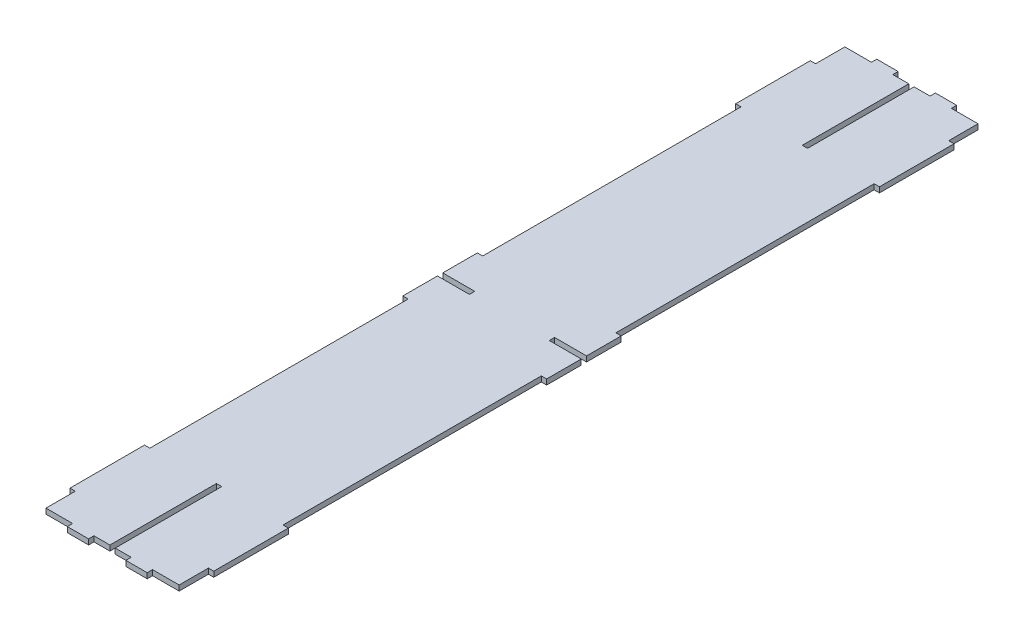
SolidWorks part; units mm, degrees
ref_plane "Front Plane" through (0, 0, 0) normal (0, 0, 1) x (1, 0, 0)
ref_plane "Top Plane" through (0, 0, 0) normal (0, 1, 0) x (1, 0, 0)
ref_plane "Right Plane" through (0, 0, 0) normal (1, 0, 0) x (0, 0, -1)
sketch "Sketch1" plane through (0, 0, 0) normal (0, 1, 0) x (1, 0, 0)
  line L5 (-12.5, 75) -> (-7.5, 75)
  line L6 (-12.5, 75) -> (12.5, 75) construction
  line L21 (-12.5, 75) -> (-12.5, -75) construction
  line L35 (-12.5, -75) -> (12.5, -75) construction
  line L84 (12.5, 75) -> (12.5, -75) construction
  line L85 (-12.5, 75) -> (12.5, -75) construction
  line L86 (-12.5, -75) -> (12.5, 75) construction
  line L87 (-7.5, 75) -> (-7.5, 76)
  line L88 (-7.5, 76) -> (-3.5, 76)
  line L89 (-3.5, 76) -> (-3.5, 75)
  line L91 (3.5, 75) -> (3.5, 76)
  line L92 (3.5, 76) -> (7.5, 76)
  line L93 (7.5, 76) -> (7.5, 75)
  line L94 (7.5, 75) -> (12.5, 75)
  line L95 (-12.5, 75) -> (-13.5, 75) construction
  line L96 (-13.5, 75) -> (-13.5, -75) construction
  line L97 (-13.5, -75) -> (-12.5, -75) construction
  line L98 (-0.5, 75) -> (-0.5, 55)
  line L99 (0, 0) -> (0, 55) construction
  line L100 (-12.5, 75) -> (-12.5, 69.5)
  line L101 (-12.5, 69.5) -> (-13.5, 69.5)
  line L102 (-13.5, 69.5) -> (-13.5, 55.5)
  line L103 (-13.5, 55.5) -> (-12.5, 55.5)
  line L104 (-12.5, 55.5) -> (-12.5, 7)
  line L105 (-12.5, 7) -> (-13.5, 7)
  line L107 (-13.5, -7) -> (-12.5, -7)
  line L108 (-12.5, -7) -> (-12.5, -55.5)
  line L109 (-12.5, -55.5) -> (-13.5, -55.5)
  line L110 (-13.5, -55.5) -> (-13.5, -69.5)
  line L111 (-13.5, -69.5) -> (-12.5, -69.5)
  line L112 (-12.5, -69.5) -> (-12.5, -75)
  line L113 (-13.5, 0) -> (-12.5, 0) construction
  line L114 (12.5, -69.5) -> (12.5, -75)
  line L119 (-0.5, 55) -> (0.5, 55)
  line L120 (0.5, 55) -> (0.5, 75)
  line L125 (-3.5, 75) -> (-0.5, 75)
  line L126 (0.5, 75) -> (3.5, 75)
  line L127 (13.5, -69.5) -> (12.5, -69.5)
  line L128 (13.5, -55.5) -> (13.5, -69.5)
  line L129 (12.5, -55.5) -> (13.5, -55.5)
  line L130 (12.5, -7) -> (12.5, -55.5)
  line L131 (13.5, -7) -> (12.5, -7)
  line L133 (12.5, 7) -> (13.5, 7)
  line L134 (12.5, 55.5) -> (12.5, 7)
  line L135 (13.5, 55.5) -> (12.5, 55.5)
  line L136 (13.5, 69.5) -> (13.5, 55.5)
  line L137 (12.5, 69.5) -> (13.5, 69.5)
  line L138 (12.5, 75) -> (12.5, 69.5)
  line L139 (7.5, -75) -> (12.5, -75)
  line L140 (7.5, -76) -> (7.5, -75)
  line L141 (3.5, -76) -> (7.5, -76)
  line L142 (3.5, -75) -> (3.5, -76)
  line L144 (-3.5, -76) -> (-3.5, -75)
  line L145 (-7.5, -76) -> (-3.5, -76)
  line L146 (-7.5, -75) -> (-7.5, -76)
  line L147 (-12.5, -75) -> (-7.5, -75)
  line L148 (0, 75) -> (0, 55) construction
  line L149 (-3.5, -75) -> (-0.5, -75)
  line L150 (-0.5, -75) -> (-0.5, -55)
  line L151 (-0.5, -55) -> (0.5, -55)
  line L152 (0.5, -55) -> (0.5, -75)
  line L153 (0.5, -75) -> (3.5, -75)
  line L154 (0, -75) -> (0, -55) construction
  line L155 (0, -55) -> (0, 0) construction
  line L156 (-13.5, 0.5) -> (-7.5, 0.5)
  line L157 (-7.5, 0.5) -> (-7.5, -0.5)
  line L158 (-7.5, -0.5) -> (-13.5, -0.5)
  line L159 (-13.5, 7) -> (-13.5, 0.5)
  line L160 (-13.5, -0.5) -> (-13.5, -7)
  line L161 (-12.5, 0) -> (-7.5, 0) construction
  line L162 (-7.5, 0) -> (0, 0) construction
  line L163 (13.5, 7) -> (13.5, 0.5)
  line L164 (13.5, 0.5) -> (7.5, 0.5)
  line L165 (7.5, 0.5) -> (7.5, -0.5)
  line L166 (7.5, -0.5) -> (13.5, -0.5)
  line L167 (13.5, -0.5) -> (13.5, -7)
  line L168 (7.5, 0) -> (0, 0) construction
  line L169 (13.5, 0.5) -> (13.5, -0.5) construction
  line L170 (7.5, 0) -> (12.5, 0) construction
  line L171 (12.5, 0) -> (13.5, 0) construction
  line L172 (-3.5, -76) -> (3.5, -76) construction
  line L173 (0, -75) -> (0, -76) construction
  line L174 (-7.5, -75) -> (-7.5, 75) construction
  point P0 (0, 0)
  point P75 (0, 0)
  point P77 (-7.5, -75.3649)
  point P78 (2.2964, -75)
  dimension "D1" = 25
  dimension "D2" = 150
  dimension "D8" = 5.5
  dimension "D13" = 20
  dimension "D3" = 5
  dimension "D4" = 5
  dimension "D5" = 4
  dimension "D6" = 4
  dimension "D7" = 1
  dimension "D9" = 14
  dimension "D10" = 5.5
  dimension "D11" = 1
  dimension "D12" = 1
  dimension "D14" = 1
  dimension "D15" = 20
  dimension "D16" = 5
  dimension "D17" = 1
  dimension "D18" = 5
  dimension "D19" = 1
  dimension "D20" = 14
  dimension "D21" = 1
  dimension "D22" = 4
extrude "Boss-Extrude1" add sketch "Sketch1" along normal blind 1
